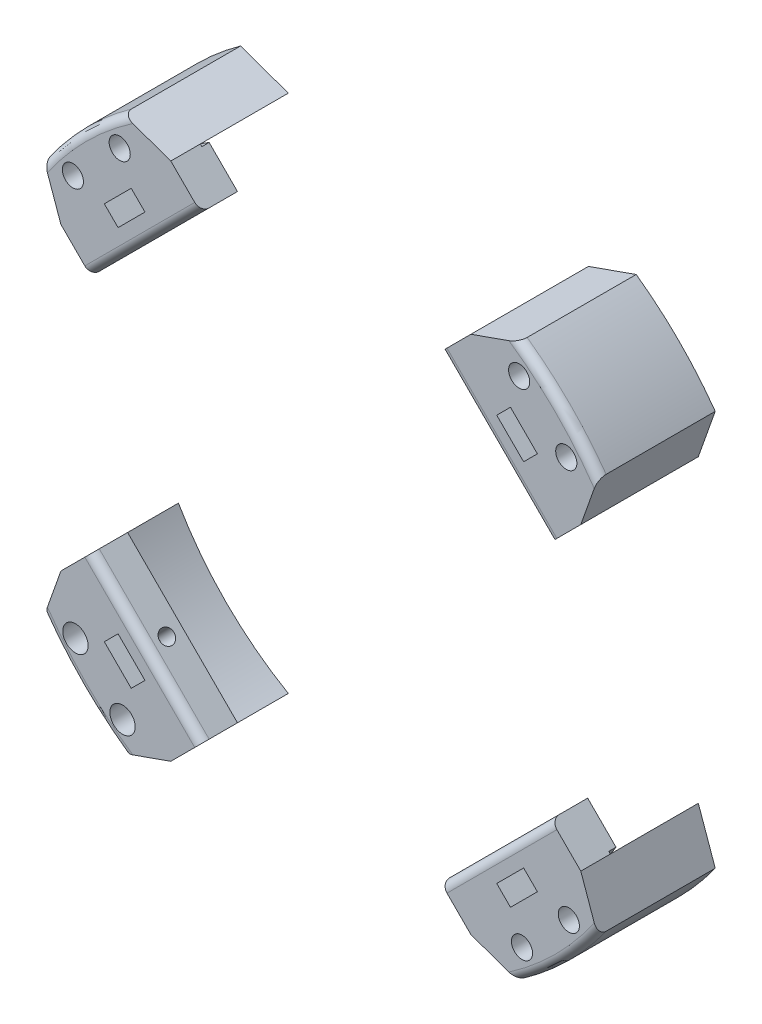
SolidWorks part; units mm, degrees
ref_plane "Front Plane" through (0, 0, 0) normal (0, 0, 1) x (1, 0, 0)
ref_plane "Top Plane" through (0, 0, 0) normal (0, 1, 0) x (1, 0, 0)
ref_plane "Right Plane" through (0, 0, 0) normal (1, 0, 0) x (0, 0, -1)
sketch "Sketch5" plane through (0, 0, 0) normal (0, 0, 1) x (1, 0, 0)
  line L0 (-45.9961, 46.8029) -> (-41.9913, 35.4939)
  line L1 (-41.7712, 34.8724) -> (-45.9961, 46.8029) construction
  line L2 (-27.3029, 65.4961) -> (-15.9939, 61.4913)
  line L3 (-15.3724, 61.2713) -> (-27.3029, 65.4961) construction
  line L4 (66.3029, 65.4961) -> (54.9939, 61.4913)
  line L5 (84.9961, 46.8029) -> (80.9913, 35.4939)
  line L6 (84.9961, -46.8029) -> (80.9913, -35.4939)
  line L7 (66.3029, -65.4961) -> (54.9939, -61.4913)
  line L8 (-27.3029, -65.4961) -> (-15.9939, -61.4913)
  line L9 (-45.9961, -46.8029) -> (-41.9913, -35.4939)
  arc A0 (-27.3029, 65.4961) -> (-45.9961, 46.8029) centre (19.5, 0) ccw
  arc A1 (-15.9939, 61.4913) -> (-41.9913, 35.4939) centre (19.5, 0) ccw
  circle A2 centre (-39.1586, 46.9103) radius 1.7
  circle A3 centre (-28.0836, 58.0553) radius 1.7
  arc A4 (84.9961, 46.8029) -> (66.3029, 65.4961) centre (19.5, 0) ccw
  arc A5 (80.9913, 35.4939) -> (54.9939, 61.4913) centre (19.5, 0) ccw
  circle A6 centre (66.4103, 58.6586) radius 1.7
  circle A7 centre (77.5553, 47.5836) radius 1.7
  arc A8 (66.3029, -65.4961) -> (84.9961, -46.8029) centre (19.5, 0) ccw
  arc A9 (54.9939, -61.4913) -> (80.9913, -35.4939) centre (19.5, 0) ccw
  circle A10 centre (78.1586, -46.9103) radius 1.7
  circle A11 centre (67.0836, -58.0553) radius 1.7
  arc A12 (-45.9961, -46.8029) -> (-27.3029, -65.4961) centre (19.5, 0) ccw
  arc A13 (-41.9913, -35.4939) -> (-15.9939, -61.4913) centre (19.5, 0) ccw
  circle A14 centre (-27.4103, -58.6586) radius 1.7
  circle A15 centre (-38.5553, -47.5836) radius 1.7
  point P45 (19.5, 0)
  dimension "D1" = 4
extrude "Boss-Extrude3" add sketch "Sketch5" along normal offset from surface (20.8 mm away) 2
sketch "Sketch6" plane through (0, 0, 20.8) normal (0, 0, 1) x (1, 0, 0)
  circle A8 centre (-38.5553, -47.5836) radius 2.5
  circle A9 centre (-27.4103, -58.6586) radius 2.5
  circle A10 centre (-28.0836, 58.0553) radius 2.5
  circle A11 centre (-39.1586, 46.9103) radius 2.5
  circle A12 centre (77.5553, 47.5836) radius 2.5
  circle A13 centre (66.4103, 58.6586) radius 2.5
  circle A14 centre (67.0836, -58.0553) radius 2.5
  circle A15 centre (78.1586, -46.9103) radius 2.5
  point P21 (19.5, 0)
  dimension "D1" = 4
extrude "Cut-Extrude3" cut sketch "Sketch6" against normal offset from surface (15.8 mm away) 5 up to face at (-33.4422, -52.9422, 0)
sketch "Sketch8" plane through (0, 0, 20.8) normal (0, 0, 1) x (1, 0, 0)
  line L0 (80.9913, -35.4939) -> (84.9961, -46.8029)
  line L1 (54.9939, -61.4913) -> (66.3029, -65.4961)
  line L2 (54.9939, -61.4913) -> (47.9228, -54.4203)
  line L3 (47.9228, -54.4203) -> (73.9203, -28.4228)
  line L4 (80.9913, -35.4939) -> (73.9203, -28.4228)
  line L5 (-15.9939, -61.4913) -> (-27.3029, -65.4961)
  line L6 (-41.9913, -35.4939) -> (-45.9961, -46.8029)
  line L7 (-41.9913, -35.4939) -> (-34.9203, -28.4228)
  line L8 (-34.9203, -28.4228) -> (-8.9228, -54.4203)
  line L9 (-15.9939, -61.4913) -> (-8.9228, -54.4203)
  line L10 (-41.9913, 35.4939) -> (-45.9961, 46.8029)
  line L11 (-15.9939, 61.4913) -> (-27.3029, 65.4961)
  line L12 (-15.9939, 61.4913) -> (-8.9228, 54.4203)
  line L13 (-8.9228, 54.4203) -> (-34.9203, 28.4228)
  line L14 (-41.9913, 35.4939) -> (-34.9203, 28.4228)
  line L15 (54.9939, 61.4913) -> (66.3029, 65.4961)
  line L16 (80.9913, 35.4939) -> (84.9961, 46.8029)
  line L17 (80.9913, 35.4939) -> (73.9203, 28.4228)
  line L18 (73.9203, 28.4228) -> (47.9228, 54.4203)
  line L19 (54.9939, 61.4913) -> (47.9228, 54.4203)
  arc A0 (66.3029, -65.4961) -> (84.9961, -46.8029) centre (19.5, 0) ccw
  circle A2 centre (67.0836, -58.0553) radius 2.5
  circle A3 centre (78.1586, -46.9103) radius 2.5
  arc A4 (-45.9961, -46.8029) -> (-27.3029, -65.4961) centre (19.5, 0) ccw
  circle A5 centre (-38.5553, -47.5836) radius 2.5
  circle A6 centre (-27.4103, -58.6586) radius 2.5
  arc A7 (-27.3029, 65.4961) -> (-45.9961, 46.8029) centre (19.5, 0) ccw
  circle A8 centre (-28.0836, 58.0553) radius 2.5
  circle A9 centre (-39.1586, 46.9103) radius 2.5
  arc A10 (84.9961, 46.8029) -> (66.3029, 65.4961) centre (19.5, 0) ccw
  circle A11 centre (77.5553, 47.5836) radius 2.5
  circle A12 centre (66.4103, 58.6586) radius 2.5
  point P51 (19.5, 0)
  dimension "D1" = 4
extrude "Boss-Extrude4" add sketch "Sketch8" along normal blind 7
sketch "Sketch9" plane through (0, 0, 27.8) normal (0, 0, 1) x (1, 0, 0)
  line L0 (-23.7325, 49.5965) -> (-22.1062, 47.9701)
  line L2 (-22.1062, 47.9701) -> (-25.2882, 44.7882)
  line L3 (-30.0965, -43.2325) -> (-28.4701, -41.6062)
  line L4 (-28.4701, -41.6062) -> (-25.2882, -44.7882)
  line L5 (-25.2882, -44.7882) -> (-22.1062, -47.9701)
  line L6 (-23.7325, -49.5965) -> (-22.1062, -47.9701)
  line L7 (-30.0965, -43.2325) -> (-31.7228, -44.8589)
  line L8 (-23.7325, -49.5965) -> (-25.3589, -51.2228)
  line L9 (-25.3589, -51.2228) -> (-31.7228, -44.8589)
  line L10 (-25.2882, 44.7882) -> (-28.4701, 41.6062)
  line L11 (-30.0965, 43.2325) -> (-28.4701, 41.6062)
  line L12 (-23.7325, 49.5965) -> (-25.3589, 51.2228)
  line L13 (-30.0965, 43.2325) -> (-31.7228, 44.8589)
  line L14 (-31.7228, 44.8589) -> (-25.3589, 51.2228)
  line L15 (69.0965, 43.2325) -> (67.4701, 41.6062)
  line L16 (67.4701, 41.6062) -> (64.2882, 44.7882)
  line L17 (64.2882, 44.7882) -> (61.1062, 47.9701)
  line L18 (62.7325, 49.5965) -> (61.1062, 47.9701)
  line L19 (69.0965, 43.2325) -> (70.7228, 44.8589)
  line L20 (62.7325, 49.5965) -> (64.3589, 51.2228)
  line L21 (64.3589, 51.2228) -> (70.7228, 44.8589)
  line L22 (62.7325, -49.5965) -> (61.1062, -47.9701)
  line L23 (61.1062, -47.9701) -> (64.2882, -44.7882)
  line L24 (64.2882, -44.7882) -> (67.4701, -41.6062)
  line L25 (69.0965, -43.2325) -> (67.4701, -41.6062)
  line L26 (62.7325, -49.5965) -> (64.3589, -51.2228)
  line L27 (69.0965, -43.2325) -> (70.7228, -44.8589)
  line L28 (70.7228, -44.8589) -> (64.3589, -51.2228)
  point P31 (19.5, 0)
  dimension "D1" = 4
extrude "Cut-Extrude4" cut sketch "Sketch9" against normal blind 7
sketch "Sketch10" plane through (-31.6715, 31.6715, 0) normal (0.7071, -0.7071, 0) x (0, 0, -1)
  line L0 (-20.8, 13.7886) -> (-22.8, 13.7886)
  line L1 (-20.8, -4.5944) -> (-20.8, 32.1716) construction
  circle A0 centre (-22.8, 13.7886) radius 1.7
extrude "Cut-Extrude5" cut sketch "Sketch10" against normal blind 16
sketch "Sketch12" plane through (0, 0, 20.8) normal (0, 0, -1) x (-1, 0, 0)
  line L0 (15.6278, -61.1252) -> (8.9228, -54.4203)
  line L1 (15.9939, -61.4913) -> (8.9228, -54.4203) construction
  line L2 (8.9228, -54.4203) -> (34.9203, -28.4228)
  line L3 (34.9203, -28.4228) -> (41.6252, -35.1278)
  line L4 (31.7228, -44.8589) -> (28.4701, -41.6062)
  line L5 (28.4701, -41.6062) -> (22.1062, -47.9701)
  line L6 (22.1062, -47.9701) -> (25.3589, -51.2228)
  line L7 (25.3589, -51.2228) -> (31.7228, -44.8589)
  line L8 (-80.6252, -35.1278) -> (-73.9203, -28.4228)
  line L9 (-73.9203, -28.4228) -> (-47.9228, -54.4203)
  line L10 (-47.9228, -54.4203) -> (-54.6278, -61.1252)
  line L11 (-64.3589, -51.2228) -> (-61.1062, -47.9701)
  line L12 (-61.1062, -47.9701) -> (-67.4701, -41.6062)
  line L13 (-67.4701, -41.6062) -> (-70.7228, -44.8589)
  line L14 (-70.7228, -44.8589) -> (-64.3589, -51.2228)
  line L15 (-54.6278, 61.1252) -> (-47.9228, 54.4203)
  line L16 (-47.9228, 54.4203) -> (-73.9203, 28.4228)
  line L17 (-73.9203, 28.4228) -> (-80.6252, 35.1278)
  line L18 (-70.7228, 44.8589) -> (-67.4701, 41.6062)
  line L19 (-67.4701, 41.6062) -> (-61.1062, 47.9701)
  line L20 (-61.1062, 47.9701) -> (-64.3589, 51.2228)
  line L21 (-64.3589, 51.2228) -> (-70.7228, 44.8589)
  line L22 (41.6252, 35.1278) -> (34.9203, 28.4228)
  line L23 (34.9203, 28.4228) -> (8.9228, 54.4203)
  line L24 (8.9228, 54.4203) -> (15.6278, 61.1252)
  line L25 (25.3589, 51.2228) -> (22.1062, 47.9701)
  line L26 (22.1062, 47.9701) -> (28.4701, 41.6062)
  line L27 (28.4701, 41.6062) -> (31.7228, 44.8589)
  line L28 (31.7228, 44.8589) -> (25.3589, 51.2228)
  arc A0 (15.6278, -61.1252) -> (41.6252, -35.1278) centre (-19.5, 0) ccw
  arc A1 (-80.6252, -35.1278) -> (-54.6278, -61.1252) centre (-19.5, 0) ccw
  arc A2 (-54.6278, 61.1252) -> (-80.6252, 35.1278) centre (-19.5, 0) ccw
  arc A3 (41.6252, 35.1278) -> (15.6278, 61.1252) centre (-19.5, 0) ccw
  point P46 (-19.5, 0)
  dimension "D1" = 4
extrude "Boss-Extrude5" add sketch "Sketch12" along normal blind 1.7
sketch "Sketch14" plane through (-31.6715, -31.6715, 0) normal (0.7071, 0.7071, 0) x (0, 0, -1)
  line L0 (-19.1, -13.7886) -> (-22.8, -13.7886)
  line L1 (-19.1, 4.5944) -> (-19.1, -32.1715) construction
  circle A0 centre (-22.8, -13.7886) radius 1.7
extrude "Cut-Extrude6" cut sketch "Sketch14" against normal offset from surface (15.3611 mm away) 6 contours A0 up to face at (-28.5409, -48.0408, 23.45) offset beyond the face yes
sketch "Sketch15" plane through (51.1715, -51.1715, 0) normal (-0.7071, 0.7071, 0) x (0, 0, 1)
  line L0 (19.1, 13.7886) -> (22.8, 13.7886)
  line L1 (19.1, -4.5944) -> (19.1, 32.1715) construction
  circle A0 centre (22.8, 13.7886) radius 1.7
extrude "Cut-Extrude7" cut sketch "Sketch15" against normal offset from surface (15.3611 mm away) 6 up to face at (67.5408, -48.0409, 23.45) offset beyond the face yes
sketch "Sketch16" plane through (51.1715, 51.1715, 0) normal (-0.7071, -0.7071, 0) x (0, 0, 1)
  line L0 (19.1, -13.7886) -> (22.8, -13.7886)
  line L1 (19.1, -32.1716) -> (19.1, 4.5944) construction
  circle A0 centre (22.8, -13.7886) radius 1.7
extrude "Cut-Extrude8" cut sketch "Sketch16" against normal offset from surface (15.3611 mm away) 6 up to face at (67.5409, 48.0408, 23.45) offset beyond the face yes
fillet "Fillet5" radius 2 1 edges at (-37.4221, 56.9221, 27.8)
fillet "Fillet6" radius 2 1 edges at (-37.4221, -56.9221, 27.8)
fillet "Fillet7" radius 2 1 edges at (76.4221, -56.9221, 27.8)
fillet "Fillet8" radius 2 1 edges at (76.4221, 56.9221, 27.8)
fillet "Fillet9" radius 2 1 edges at (-21.9215, 41.4215, 27.8)
fillet "Fillet10" radius 2 1 edges at (60.9215, 41.4215, 27.8)
fillet "Fillet11" radius 2 1 edges at (60.9215, -41.4215, 27.8)
fillet "Fillet12" radius 2 1 edges at (-21.9215, -41.4215, 27.8)
sketch "Sketch17" plane through (0, 0, 27.8) normal (0, 0, 1) x (1, 0, 0)
  circle A0 centre (-38.5553, -47.5836) radius 3
  circle A1 centre (-27.4103, -58.6586) radius 3
  dimension "D1" = 6
extrude "Cut-Extrude9" cut sketch "Sketch17" against normal up to surface (22.8 mm away) up to face at (-36.8553, -47.5836, 5)
